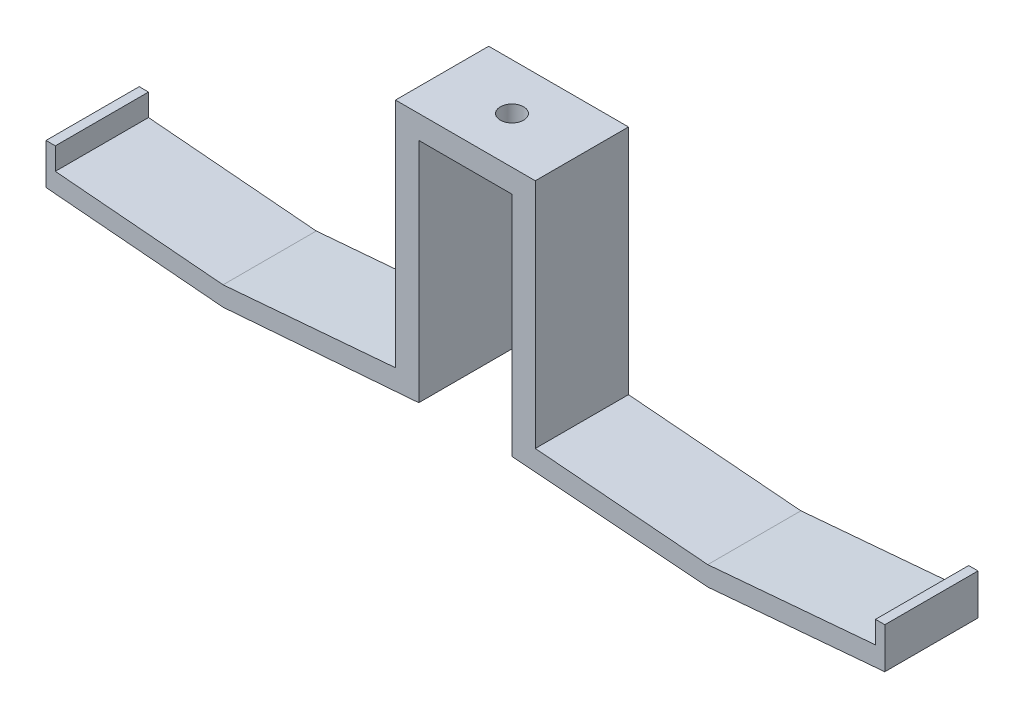
SolidWorks part; units mm, degrees
material "Nylon 6/10"
ref_plane "Front Plane" through (0, 0, 0) normal (0, 0, 1) x (1, 0, 0)
ref_plane "Top Plane" through (0, 0, 0) normal (0, 1, 0) x (1, 0, 0)
ref_plane "Right Plane" through (0, 0, 0) normal (1, 0, 0) x (0, 0, -1)
other "Center of Mass"
sketch "Sketch2" plane through (0, 0, 0) normal (0, 0, 1) x (1, 0, 0)
  line L1 (12.7, 0) -> (12.7, -61.918)
  line L2 (12.7, -61.918) -> (66.04, -66.0514)
  line L3 (66.04, -66.0514) -> (114.3, -61.918)
  line L4 (114.3, -61.918) -> (114.3, -50.8114)
  line L5 (111.76, -50.8114) -> (111.76, -56.838)
  line L6 (111.76, -56.838) -> (66.04, -60.7538)
  line L19 (114.3, -50.8114) -> (111.76, -50.8114)
  line L20 (0, 125.2351) -> (0, -75.9356) construction
  line L21 (12.7, 0) -> (-12.7, 0)
  line L22 (0, 0) -> (0, 6.35)
  line L23 (19.05, 6.35) -> (-19.05, 6.35)
  line L24 (19.05, 6.35) -> (19.05, 0)
  line L25 (19.05, 0) -> (19.05, -56.838)
  line L26 (19.05, -56.838) -> (66.04, -60.7538)
  line L27 (-19.05, 0) -> (-19.05, -56.838)
  line L28 (-19.05, 6.35) -> (-19.05, 0)
  line L29 (-12.7, 0) -> (-12.7, -61.918)
  line L30 (-12.7, -61.918) -> (-66.04, -66.0514)
  line L31 (-66.04, -66.0514) -> (-114.3, -61.918)
  line L32 (-114.3, -61.918) -> (-114.3, -50.8114)
  line L33 (-114.3, -50.8114) -> (-111.76, -50.8114)
  line L34 (-111.76, -50.8114) -> (-111.76, -56.838)
  line L35 (-111.76, -56.838) -> (-66.04, -60.7538)
  line L36 (-19.05, -56.838) -> (-66.04, -60.7538)
  dimension "D1" = 19.05
  dimension "D2" = 12.7
  dimension "D3" = 56.838
  dimension "D4" = 3.9158
  dimension "D5" = 61.918
  dimension "D6" = 2.54
  dimension "D7" = 45.72
  dimension "D8" = 46.99
  dimension "D9" = 15.24
  dimension "D10" = 6.35
extrude "Boss-Extrude1" add sketch "Sketch2" along normal blind 25.4 contours L26 L25 L24 L23 L22 L21 L1 L2 L3 L4 L19 L5 L6 | L27 L36 L35 L34 L33 L32 L31 L30 L29 L21 L22 L23 L28
hole_wizard "1/4 (0.25) Diameter Hole1" positions "Sketch3" profile "Sketch4" hole size "1/4" standard "ANSI Inch"
sketch "Sketch3" plane through (0, 6.35, 0) normal (0, 1, 0) x (1, 0, 0)
  line L0 (-19.05, -25.4) -> (-19.05, 0) construction
  line L2 (19.05, 0) -> (-19.05, 0) construction
  point P0 (0, -12.7)
  dimension "D1" = 19.05
  dimension "D2" = 12.7
sketch "Sketch4" plane through (0, 6.35, 12.7) normal (1, 0, 0) x (0, 0, 1)
  line L0 (0, 0) -> (0, 52.7077)
  line L1 (0, 52.7077) -> (3.175, 50.8)
  line L2 (3.175, 50.8) -> (3.175, 0)
  line L5 (3.175, 0) -> (0, 0)
  line L10 (0, 52.7077) -> (-3.175, 50.8) construction
  line L11 (0, -6.35) -> (0, 107.95) construction
  dimension "Hole Dia." = 6.35
  dimension "Hole Depth" = 50.8
  dimension "Drill Angle" = 118
